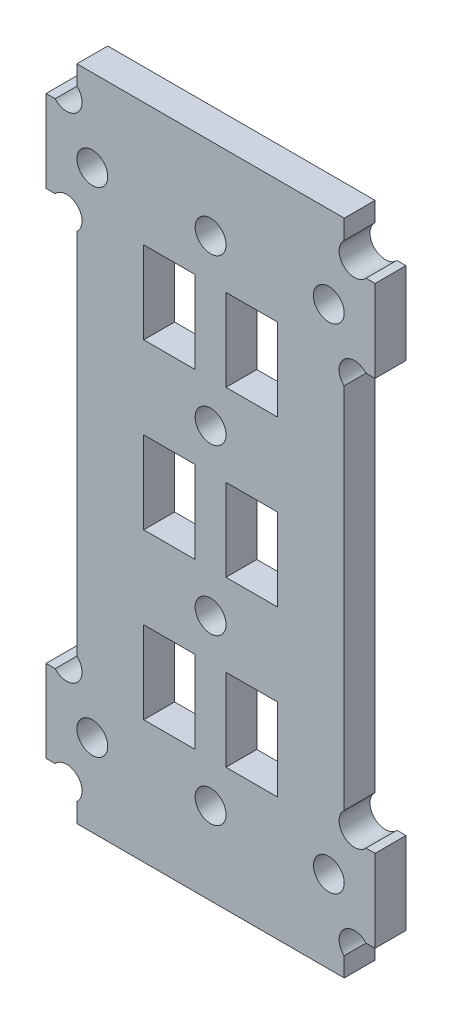
SolidWorks part; units mm, degrees
material "Thornel Mat VMA"
ref_plane "前视基准面" through (0, 0, 0) normal (0, 0, 1) x (1, 0, 0)
ref_plane "上视基准面" through (0, 0, 0) normal (0, 1, 0) x (1, 0, 0)
ref_plane "右视基准面" through (0, 0, 0) normal (1, 0, 0) x (0, 0, -1)
sketch "草图1" plane through (0, 0, 0) normal (0, 0, 1) x (1, 0, 0)
  line L1 (-16, -32) -> (16, -32)
  line L2 (-16, -32) -> (-16, 32)
  line L3 (-16, 32) -> (16, 32)
  line L4 (16, -32) -> (16, 32)
  line L5 (-16, -32) -> (16, 32) construction
  line L6 (-16, 32) -> (16, -32) construction
  point P0 (0, 0)
  dimension "D1" = 32
  dimension "D2" = 64
extrude "凸台-拉伸1" add sketch "草图1" along normal blind 3
sketch "草图2" plane through (0, 0, 3) normal (0, 0, 1) x (1, 0, 0)
  line L1 (-4, -16) -> (4, -16)
  line L2 (-4, -16) -> (-4, 16)
  line L3 (-4, 16) -> (4, 16)
  line L4 (4, -16) -> (4, 16)
  line L5 (-4, -16) -> (4, 16) construction
  line L6 (-4, 16) -> (4, -16) construction
  line L7 (1.5, 12) -> (6.5, 12)
  line L8 (1.5, 12) -> (1.5, 20)
  line L9 (1.5, 20) -> (6.5, 20)
  line L10 (6.5, 12) -> (6.5, 20)
  line L11 (1.5, 12) -> (6.5, 20) construction
  line L12 (1.5, 20) -> (6.5, 12) construction
  point P0 (0, 0)
  dimension "D1" = 5
  dimension "D2" = 8
  dimension "D3" = 8
  dimension "D4" = 32
extrude "切除-拉伸1" cut sketch "草图2" against normal through all contours L7 L10 L9 L8 L3 L4 | L8 L7 L4 L3
mirror "镜向1" about plane through (0, 0, 0) normal (1, 0, 0) of "切除-拉伸1"
mirror "镜向2" about plane through (0, 0, 0) normal (0, 1, 0) of "镜向1", "切除-拉伸1"
sketch "草图4" plane through (0, 0, 3) normal (0, 0, 1) x (1, 0, 0)
  line L0 (16, -32) -> (16, 32) construction
  line L1 (16, -4) -> (13, -4)
  line L2 (16, -4) -> (16, 4)
  line L3 (16, 4) -> (13, 4)
  line L4 (13, -4) -> (13, 4)
  point P6 (13, 0)
  dimension "D1" = 3
  dimension "D2" = 8
extrude "切除-拉伸3" cut sketch "草图4" against normal blind 10
mirror "镜向5" about plane through (0, 0, 0) normal (1, 0, 0) of "切除-拉伸3"
sketch "草图6" plane through (0, 0, 3) normal (0, 0, 1) x (1, 0, 0)
  line L1 (16, 32) -> (13, 32)
  line L2 (16, 32) -> (16, 28)
  line L3 (16, 28) -> (13, 28)
  line L4 (13, 32) -> (13, 28)
  dimension "D1" = 3
  dimension "D2" = 28
extrude "切除-拉伸5" cut sketch "草图6" against normal through all
mirror "镜向8" about plane through (0, 0, 0) normal (0, 1, 0) of "切除-拉伸5"
mirror "镜向9" about plane through (0, 0, 0) normal (1, 0, 0) of "镜向8", "切除-拉伸5"
sketch "草图8" plane through (0, 0, 3) normal (0, 0, 1) x (1, 0, 0)
  line L0 (13, 28) -> (16, 28) construction
  line L2 (13, 32) -> (13, 28) construction
  circle A0 centre (14, 29) radius 1.5
  dimension "D3" = 3
  dimension "D1" = 1
  dimension "D2" = 1
extrude "切除-拉伸6" cut sketch "草图8" against normal through all
mirror "镜向10" about plane through (0, 0, 0) normal (1, 0, 0) of "切除-拉伸6"
mirror "镜向11" about plane through (0, 0, 0) normal (0, 1, 0) of "镜向10", "切除-拉伸6"
sketch "草图10" plane through (0, 0, 3) normal (0, 0, 1) x (1, 0, 0)
  line L0 (-16, 4) -> (-13, 4) construction
  line L1 (-13, 4) -> (-13, -4) construction
  circle A0 centre (-14, 3) radius 1.5
  point P6 (-13, 0)
  dimension "D1" = 1
  dimension "D2" = 1
  dimension "D3" = 3
extrude "切除-拉伸8" cut sketch "草图10" against normal through all
mirror "镜向14" about plane through (0, 0, 0) normal (0, 1, 0) of "切除-拉伸8"
mirror "镜向15" about plane through (0, 0, 0) normal (1, 0, 0) of "镜向14", "切除-拉伸8"
sketch "草图11" plane through (0, 0, 3) normal (0, 0, 1) x (1, 0, 0)
  circle A0 centre (-11.5, -8) radius 1.5
  circle A1 centre (-11.5, -24) radius 1.5
  dimension "D1" = 3
  dimension "D2" = 3
  dimension "D3" = 11.5
  dimension "D4" = 8
  dimension "D5" = 16
extrude "切除-拉伸9" cut sketch "草图11" against normal through all
mirror "镜向16" about plane through (0, 0, 0) normal (1, 0, 0) of "切除-拉伸9"
mirror "镜向17" about plane through (0, 0, 0) normal (0, 1, 0) of "切除-拉伸9", "镜向16"
sketch "草图12" plane through (0, 0, 0) normal (0, 0, -1) x (-1, 0, 0)
  line L0 (-16, 4) -> (-16, 28) construction
  line L1 (-16, 12) -> (-13, 12)
  line L2 (-16, 12) -> (-16, 20)
  line L3 (-16, 20) -> (-13, 20)
  line L4 (-13, 12) -> (-13, 20)
  dimension "D1" = 8
  dimension "D2" = 3
  dimension "D3" = 12
extrude "切除-拉伸10" cut sketch "草图12" against normal through all
mirror "镜向18" about plane through (0, 0, 0) normal (1, 0, 0) of "切除-拉伸10"
mirror "镜向19" about plane through (0, 0, 0) normal (0, 1, 0) of "切除-拉伸10", "镜向18"
sketch "草图13" plane through (0, 0, 0) normal (0, 0, -1) x (-1, 0, 0)
  line L0 (-13, 12) -> (-13, 20) construction
  line L1 (-16, 12) -> (-13, 12) construction
  line L2 (-13, 20) -> (-16, 20) construction
  circle A0 centre (-14, 19) radius 1.5
  circle A1 centre (-14, 13) radius 1.5
  dimension "D1" = 1
  dimension "D2" = 3
  dimension "D3" = 3
  dimension "D4" = 1
  dimension "D5" = 1
  dimension "D6" = 1
extrude "切除-拉伸11" cut sketch "草图13" against normal through all
mirror "镜向20" about plane through (0, 0, 0) normal (1, 0, 0) of "切除-拉伸11"
mirror "镜向21" about plane through (0, 0, 0) normal (0, 1, 0) of "镜向20", "切除-拉伸11"
sketch "草图14" plane through (0, 0, 0) normal (0, 0, -1) x (-1, 0, 0)
  line L1 (1.5, -4) -> (6.5, -4)
  line L2 (1.5, -4) -> (1.5, 4)
  line L3 (1.5, 4) -> (6.5, 4)
  line L4 (6.5, -4) -> (6.5, 4)
  line L5 (1.5, -4) -> (6.5, 4) construction
  line L6 (1.5, 4) -> (6.5, -4) construction
  point P0 (4, 0)
  dimension "D1" = 5
  dimension "D2" = 8
  dimension "D3" = 1.5
extrude "切除-拉伸12" cut sketch "草图14" against normal through all
mirror "镜向22" about plane through (0, 0, 0) normal (1, 0, 0) of "切除-拉伸12"
sketch "草图15" plane through (0, 0, 0) normal (0, 0, -1) x (-1, 0, 0)
  circle A0 centre (0, 8) radius 1.5
  circle A1 centre (0, 24) radius 1.5
  dimension "D1" = 3
  dimension "D2" = 3
  dimension "D3" = 8
  dimension "D4" = 24
extrude "切除-拉伸13" cut sketch "草图15" against normal through all
mirror "镜向23" about plane through (0, 0, 0) normal (0, 1, 0) of "切除-拉伸13"
sketch "草图16" plane through (0, 0, 0) normal (0, 0, -1) x (-1, 0, 0)
  circle A0 centre (11.5, 8) radius 1.5
  circle A1 centre (-11.5, 8) radius 1.5
  circle A2 centre (-11.5, -8) radius 1.5
  circle A3 centre (11.5, -8) radius 1.5
extrude "凸台-拉伸2" add sketch "草图16" against normal up to surface (3 mm away) up to face at (-1.5, -24, 3)
sketch "草图17" plane through (0, 0, 3) normal (0, 0, 1) x (1, 0, 0)
  circle A0 centre (14, 13) radius 1.5
  circle A1 centre (14, 3) radius 1.5
  circle A2 centre (14, -3) radius 1.5
  circle A3 centre (14, -13) radius 1.5
  circle A4 centre (-14, -13) radius 1.5
  circle A5 centre (-14, -3) radius 1.5
  circle A6 centre (-14, 3) radius 1.5
  circle A7 centre (-14, 13) radius 1.5
extrude "凸台-拉伸3" add sketch "草图17" against normal up to surface (3 mm away) up to face at (-1.5, -24, 0)
sketch "草图18" plane through (0, 0, 3) normal (0, 0, 1) x (1, 0, 0)
  line L0 (13, 14.118) -> (13, 17.882) construction
  line L1 (13, 15.51) -> (16.6718, 15.51)
  line L2 (13, 15.51) -> (13, -15.1614)
  line L3 (13, -15.1614) -> (16.6718, -15.1614)
  line L4 (16.6718, 15.51) -> (16.6718, -15.1614)
  line L5 (-13, 14.118) -> (-13, 17.882) construction
  line L6 (-13, 15.51) -> (-16.9041, 15.51)
  line L7 (-13, 15.51) -> (-13, -15.1614)
  line L8 (-13, -15.1614) -> (-16.9041, -15.1614)
  line L9 (-16.9041, 15.51) -> (-16.9041, -15.1614)
extrude "切除-拉伸14" cut sketch "草图18" against normal through all
